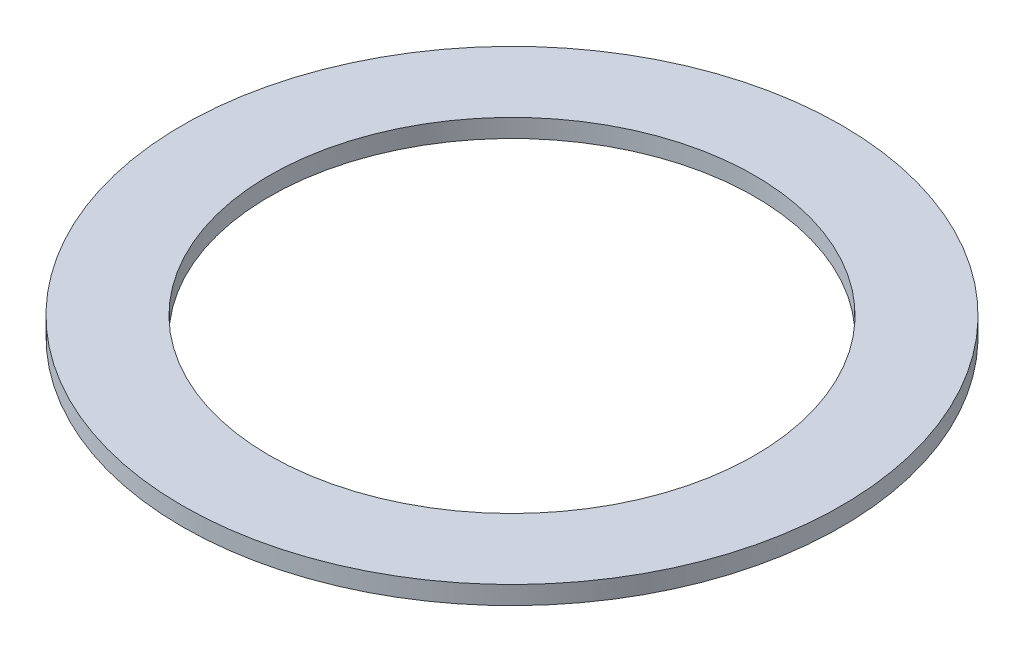
SolidWorks part; units mm, degrees
ref_plane "Front Plane" through (0, 0, 0) normal (0, 0, 1) x (1, 0, 0)
ref_plane "Top Plane" through (0, 0, 0) normal (0, 1, 0) x (1, 0, 0)
ref_plane "Right Plane" through (0, 0, 0) normal (1, 0, 0) x (0, 0, -1)
sketch "Sketch1" plane through (0, 0, 0) normal (0, 1, 0) x (1, 0, 0)
  circle A1 centre (0, 0) radius 36
  circle A2 centre (0, 0) radius 26.5
  dimension "D1" = 72
  dimension "D2" = 53
extrude "Boss-Extrude1" add sketch "Sketch1" along normal blind 2
